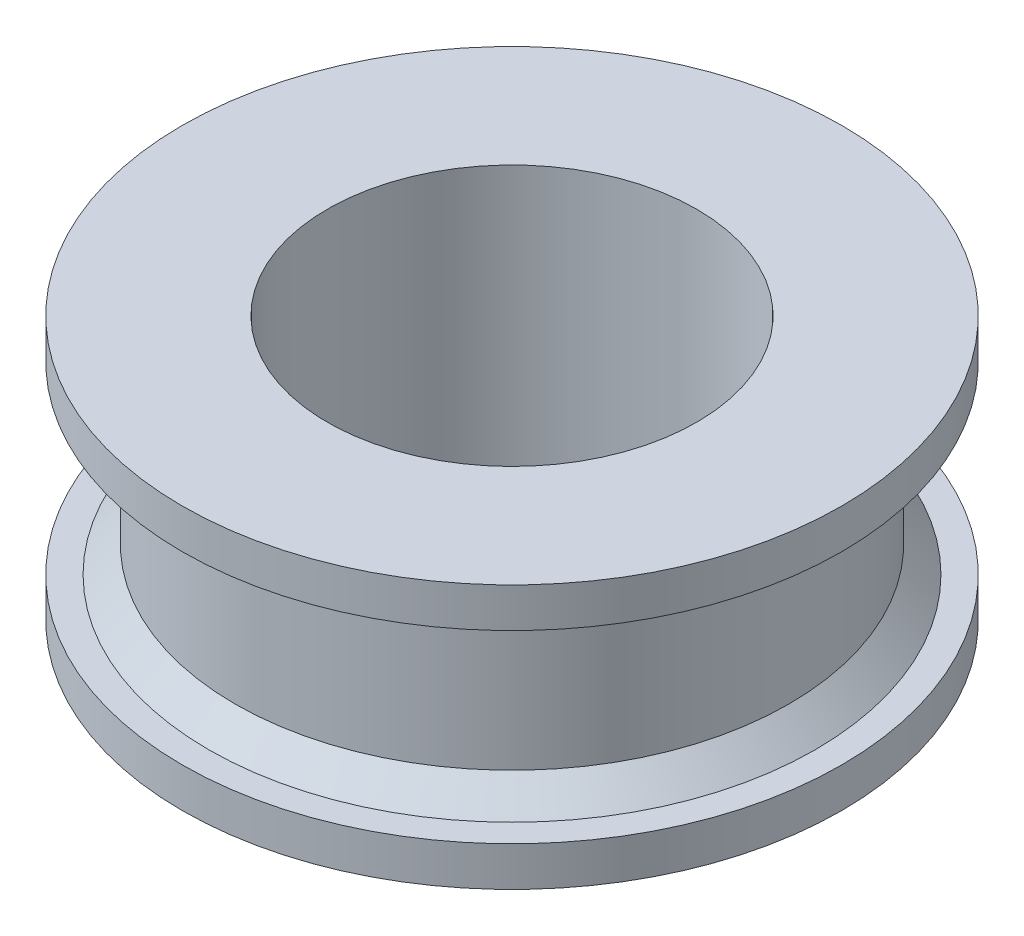
SolidWorks part; units mm, degrees
ref_plane "Front Plane" through (0, 0, 0) normal (0, 0, 1) x (1, 0, 0)
ref_plane "Top Plane" through (0, 0, 0) normal (0, 1, 0) x (1, 0, 0)
ref_plane "Right Plane" through (0, 0, 0) normal (1, 0, 0) x (0, 0, -1)
other "Default"
sketch "Sketch1" plane through (0, 0, 0) normal (0, 0, 1) x (1, 0, 0)
  line L0 (0, -14.8448) -> (0, 19.9138) construction
  line L1 (7, -5) -> (7, 5)
  line L2 (7, 5) -> (12.5, 5)
  line L3 (12.5, 5) -> (12.5, 3.5)
  line L4 (12.5, 3.5) -> (11.5, 3.5)
  line L5 (11.5, 3.5) -> (10.5, 2.5)
  line L6 (10.5, 2.5) -> (10.5, -2.5)
  line L7 (10.5, -2.5) -> (11.5, -3.5)
  line L8 (11.5, -3.5) -> (12.5, -3.5)
  line L9 (12.5, -3.5) -> (12.5, -5)
  line L10 (12.5, -5) -> (7, -5)
  point P8 (7, 0)
  point P14 (10.5, 0)
  dimension "ID" = 14
  dimension "InnerGrooveWidth" = 5
  dimension "OuterGrooveWidth" = 7
  dimension "OD" = 25
  dimension "Height" = 10
  dimension "GrooveDepth" = 2
revolve "Revolve1" add sketch "Sketch1" angle 360 about L0
